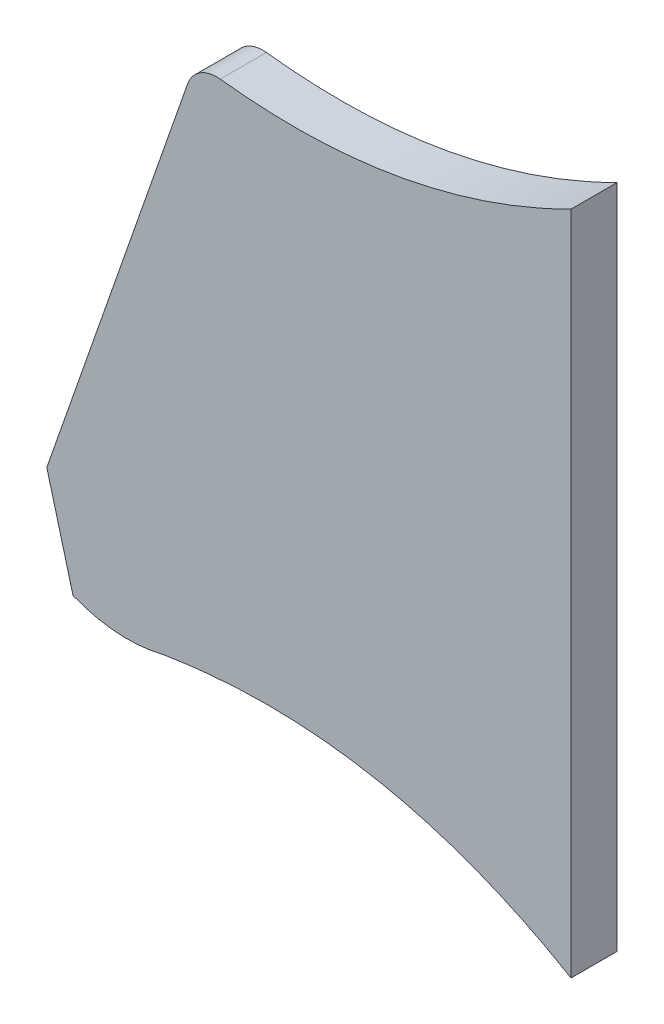
SolidWorks part; units mm, degrees
ref_plane "前视基准面" through (0, 0, 0) normal (0, 0, 1) x (1, 0, 0)
ref_plane "上视基准面" through (0, 0, 0) normal (0, 1, 0) x (1, 0, 0)
ref_plane "右视基准面" through (0, 0, 0) normal (1, 0, 0) x (0, 0, -1)
sketch "草图1" plane through (0, 0, 0) normal (0, 0, 1) x (1, 0, 0)
  line L0 (18.4197, -31.18) -> (-18.9977, -2.6487)
  line L1 (-4.1273, 31.6164) -> (18.9977, 31.6164)
  line L2 (-18.9977, -2.6487) -> (-11.5165, 31.6164)
  line L3 (-4.1273, 31.6164) -> (-11.5165, 31.6164)
  line L4 (18.9977, -31.6164) -> (18.4197, -31.18)
  line L5 (18.9977, -31.6164) -> (18.9977, 31.6164)
extrude "凸台-拉伸1" add sketch "草图1" along normal blind 3
sketch "草图2" plane through (0, 0, 3) normal (0, 0, 1) x (1, 0, 0)
  line L0 (18.9977, 31.6164) -> (18.9977, 39.6164)
  line L1 (18.9977, 39.6164) -> (-11.5165, 31.6164)
  line L2 (-11.5165, 31.6164) -> (18.9977, 31.6164)
  dimension "D1" = 8
extrude "凸台-拉伸2" add sketch "草图2" against normal up to surface (3 mm away) up to face at (5.1802, -0.4425, 0)
sketch "草图3" plane through (0, 0, 3) normal (0, 0, 1) x (1, 0, 0)
  line L0 (-18.9977, -2.6487) -> (18.4197, -31.18) construction
  line L1 (-18.9977, -2.6487) -> (18.4197, -31.18)
  line L2 (18.4197, -31.18) -> (18.9977, -31.6164) construction
  line L3 (18.4197, -31.18) -> (18.9977, -31.6164)
  spline S0 degree 3 poles (-18.9977, -2.6487) (-4.9094, -6.6648) (12.9602, -16.654) (18.9977, -31.6164) knots 0 0 0 0 0.839418 0.839418 0.839418 0.839418
extrude "切除-拉伸1" cut sketch "草图3" against normal blind 10
sketch "草图4" plane through (0, 0, 3) normal (0, 0, 1) x (1, 0, 0)
  line L0 (18.9977, 39.6164) -> (-11.5165, 31.6164) construction
  line L1 (18.9977, 39.6164) -> (-11.5165, 31.6164)
  spline S0 degree 2 poles (-11.5165, 31.6164) (5.4512, 29.7877) (18.9977, 39.6164) knots 0 0 0 1 1 1
extrude "切除-拉伸2" cut sketch "草图4" against normal blind 10
fillet "圆角1" radius 2 2 edges
sketch "草图5" plane through (0, 0, 3) normal (0, 0, 1) x (1, 0, 0)
  line L0 (-11.893, 29.892) -> (-18.6023, -0.8377) construction
  line L1 (-15.2477, 14.5271) -> (-18.6023, -0.8377)
  line L2 (-15.2477, 14.5271) -> (-5.3496, -8.0356)
  arc A2 (-18.6023, -0.8377) -> (-17.2465, -3.1728) centre (-16.6484, -1.2644) ccw construction
  arc A3 (-18.6023, -0.8377) -> (-17.2465, -3.1728) centre (-16.6484, -1.2644) ccw
  spline S0 degree 3 poles (-2928.8472, -519.4366) (3261.8242, -52.6008) (-3274.341, 435.7639) (2901.1179, -683.4599) knots -4.305527 -4.305527 -4.305527 -4.305527 5.571871 5.571871 5.571871 5.571871 only from (18.9977, -31.6164) to (-17.2465, -3.1728) construction
  spline S1 degree 3 poles (-5.3496, -8.0356) (-9.3409, -6.0038) (-13.4058, -4.3765) (-17.2465, -3.1728) knots 0.580679 0.580679 0.580679 0.580679 0.804995 0.804995 0.804995 0.804995
extrude "切除-拉伸3" cut sketch "草图5" against normal blind 10
sketch "草图6" plane through (0, 0, 3) normal (0, 0, 1) x (1, 0, 0)
  line L0 (18.9977, -31.6164) -> (18.9977, 39.6164) construction
  line L1 (18.9977, -31.6164) -> (18.9977, -24.042)
  spline S0 degree 3 poles (-2928.7675, -519.4306) (3265.9626, -52.2803) (-3283.1776, 436.4209) (2913.6883, -685.7371) knots -4.305484 -4.305484 -4.305484 -4.305484 5.578563 5.578563 5.578563 5.578563 only from (18.9977, -31.6164) to (-5.3496, -8.0356) construction
  spline S1 degree 3 poles (18.9977, -31.6164) (14.8212, -21.2659) (4.9826, -13.2953) (-5.3496, -8.0356) knots 0 0 0 0 0.580679 0.580679 0.580679 0.580679
  spline S2 degree 2 poles (-5.3496, -8.0356) (10.7128, -10.6039) (18.9977, -24.042) knots 0 0 0 1 1 1
extrude "切除-拉伸4" cut sketch "草图6" against normal blind 10
sketch "草图7" plane through (0, 0, 3) normal (0, 0, 1) x (1, 0, 0)
  line L0 (-5.3496, -8.0356) -> (-15.2477, 14.5271) construction
  line L1 (-5.3496, -8.0356) -> (-7.5011, -3.1311)
  line L2 (18.9977, -24.042) -> (18.9977, 39.6164) construction
  line L3 (18.9977, -24.042) -> (18.9977, 39.6164)
  parabola Q0 (18.9977, -24.042) -> (-5.3496, -8.0356) focus (0.5756, -26.9247) apex (9.8018, -14.0303) construction
  parabola Q1 (18.9977, -24.042) -> (-5.3496, -8.0356) focus (0.5756, -26.9247) apex (9.8018, -14.0303)
  spline S0 degree 2 poles (-7.5011, -3.1311) (8.5342, -3.7064) (18.9977, -15.7287) knots 0 0 0 1 1 1
  line M1 (-15.2477, 14.5271) -> (-5.3496, -8.0356)
  spline M2 degree 2 poles (18.9977, -24.042) (10.7128, -10.6039) (-5.3496, -8.0356) knots 0 0 0 1 1 1
  line M3 (18.9977, -24.042) -> (18.9977, 39.6164)
extrude "切除-拉伸5" cut sketch "草图7" against normal blind 10 contours S0 M1 M2 M3
sketch "草图9" plane through (0, 0, 3) normal (0, 0, 1) x (1, 0, 0)
  line L0 (-15.2477, 14.5271) -> (-5.3931, 31.338)
  line L1 (-11.893, 29.892) -> (-15.2477, 14.5271) construction
  line L2 (-11.893, 29.892) -> (-15.2477, 14.5271)
  arc A0 (-9.7926, 31.4601) -> (-11.893, 29.892) centre (-9.9391, 29.4654) ccw construction
  arc A1 (-9.7926, 31.4601) -> (-11.893, 29.892) centre (-9.9391, 29.4654) ccw
  parabola Q0 (-9.7926, 31.4601) -> (18.9977, 39.6164) focus (-0.0193, 52.6524) apex (5.7423, 33.0205) construction
  parabola Q1 (-9.7926, 31.4601) -> (18.9977, 39.6164) focus (-0.0193, 52.6524) apex (5.7423, 33.0205) construction
  parabola Q2 (-9.7926, 31.4601) -> (-5.3931, 31.338) focus (-0.0193, 52.6524) apex (5.7423, 33.0205)
extrude "切除-拉伸6" cut sketch "草图9" against normal blind 10
sketch "草图10" plane through (0, 0, 3) normal (0, 0, 1) x (1, 0, 0)
  line L0 (-15.2477, 14.5271) -> (-5.3931, 31.338) construction
  line L1 (-15.2477, 14.5271) -> (-5.3931, 31.338)
  line L2 (-5.3931, 31.338) -> (-13.424, 10.37)
  line L3 (-7.5011, -3.1311) -> (-15.2477, 14.5271) construction
  line L4 (-13.424, 10.37) -> (-15.2477, 14.5271)
extrude "切除-拉伸7" cut sketch "草图10" against normal blind 10
sketch "草图11" plane through (0, 0, 3) normal (0, 0, 1) x (1, 0, 0)
  line L0 (-7.5011, -3.1311) -> (-13.424, 10.37) construction
  line L1 (-7.5011, -3.1311) -> (-13.424, 10.37)
  line L2 (-13.424, 10.37) -> (-5.3931, 31.338) construction
  line L3 (-13.424, 10.37) -> (-5.3931, 31.338)
  line L4 (-7.5011, -3.1311) -> (-13.424, 3.6194)
  line L5 (-13.424, 3.6194) -> (-13.424, 16.6194)
  line L6 (-13.424, 16.6194) -> (-5.3931, 31.338)
  line M2 (-5.3931, 31.338) -> (-13.424, 10.37)
  line M3 (-13.424, 10.37) -> (-7.5011, -3.1311)
extrude "凸台-拉伸3" add sketch "草图11" against normal up to surface (3 mm away) contours L5 L4 M3 | L6 L5 M2 up to face at (7.6352, 9.9734, 0)
sketch "草图12" plane through (0, 0, 3) normal (0, 0, 1) x (1, 0, 0)
  line L0 (18.9977, -15.7287) -> (18.9977, -16.3787)
  parabola Q0 (-7.5011, -3.1311) -> (18.9977, -15.7287) focus (0.0241, -21.9021) apex (7.4222, -6.7033) construction
  parabola Q1 (-7.5011, -3.1311) -> (18.9977, -15.7287) focus (0.0241, -21.9021) apex (7.4222, -6.7033)
  spline S0 degree 2 poles (-7.5011, -3.1311) (8.2316, -4.862) (18.9977, -16.3787) knots 0 0 0 1 1 1
extrude "凸台-拉伸4" add sketch "草图12" against normal up to surface (3 mm away) up to face at (3.2804, 5.857, 0)
sketch "草图14" plane through (0, 0, 3) normal (0, 0, 1) x (1, 0, 0)
  line L0 (-13.424, 16.6194) -> (-5.3931, 31.338) construction
  line L1 (-13.424, 16.6194) -> (-5.3931, 31.338)
  line L2 (-13.424, 3.6194) -> (-13.424, 16.6194) construction
  line L3 (-13.424, 3.6194) -> (-13.424, 16.6194)
  line L4 (-7.5011, -3.1311) -> (-13.424, 3.6194) construction
  line L5 (-7.5011, -3.1311) -> (-13.424, 3.6194)
  line L6 (-7.5011, -3.1311) -> (-15.0881, 3.6194)
  line L7 (-15.0881, 3.6194) -> (-15.0881, 18.6192)
  line L8 (-15.0881, 18.6192) -> (-5.3931, 31.338)
extrude "凸台-拉伸5" add sketch "草图14" against normal up to surface (3 mm away) up to face at (-1.136, 7.8483, 0)
sketch "草图15" plane through (0, 0, 3) normal (0, 0, 1) x (1, 0, 0)
  line L0 (-5.3931, 31.338) -> (-15.0881, 18.6192) construction
  line L1 (-5.3931, 31.338) -> (-15.0881, 18.6192)
  line L2 (-5.3931, 31.338) -> (-15.0881, 14.4684)
  line L3 (-15.0881, 18.6192) -> (-15.0881, 3.6194) construction
  line L4 (-15.0881, 14.4684) -> (-15.0881, 18.6192)
extrude "切除-拉伸8" cut sketch "草图15" against normal blind 10
sketch "草图16" plane through (0, 0, 3) normal (0, 0, 1) x (1, 0, 0)
  line L0 (18.9977, -16.3787) -> (18.9977, 39.6164) construction
  line L1 (18.9977, -16.3787) -> (18.9977, -10.9026)
  parabola Q0 (-7.5011, -3.1311) -> (18.9977, -16.3787) focus (-1.8424, -25.2466) apex (7.2064, -7.4175) construction
  parabola Q1 (-7.5011, -3.1311) -> (18.9977, -16.3787) focus (-1.8424, -25.2466) apex (7.2064, -7.4175)
  spline S0 degree 2 poles (-7.5011, -3.1311) (7.0935, -2.5935) (18.9977, -10.9026) knots 0 0 0 1 1 1
extrude "切除-拉伸9" cut sketch "草图16" against normal blind 10
sketch "草图17" plane through (0, 0, 3) normal (0, 0, 1) x (1, 0, 0)
  line L0 (18.9977, -10.9026) -> (18.9977, 39.6164) construction
  line L1 (18.9977, -10.9026) -> (18.9977, -8.0852)
  parabola Q0 (18.9977, -10.9026) -> (-7.5011, -3.1311) focus (0.816, -24.646) apex (6.8143, -4.9227) construction
  parabola Q1 (18.9977, -10.9026) -> (-7.5011, -3.1311) focus (0.816, -24.646) apex (6.8143, -4.9227)
  spline S0 degree 2 poles (-7.5011, -3.1311) (6.6872, -0.8041) (18.9977, -8.0852) knots 0 0 0 1 1 1
extrude "切除-拉伸10" cut sketch "草图17" against normal blind 10
sketch "草图18" plane through (0, 0, 3) normal (0, 0, 1) x (1, 0, 0)
  line L0 (-15.0881, 3.6194) -> (-13.381, -2.7449)
  line L6 (-15.0881, 3.6194) -> (-7.5011, -3.1311) construction
  line L7 (-15.0881, 3.6194) -> (-7.5011, -3.1311)
  spline S0 degree 2 poles (-13.381, -2.7449) (-10.489, -3.877) (-7.5011, -3.1311) knots 0 0 0 1 1 1
extrude "凸台-拉伸7" add sketch "草图18" against normal up to surface (3 mm away) up to face at (-0.8458, 12.0669, 0)
sketch "草图19" plane through (0, 0, 3) normal (0, 0, 1) x (1, 0, 0)
  line L0 (-15.0881, 14.4684) -> (-5.3931, 31.338) construction
  line L1 (-15.0881, 14.4684) -> (-13.5933, 17.0694)
  line L2 (-15.0881, 14.4684) -> (-15.0881, 3.6194) construction
  line L3 (-15.0881, 14.4684) -> (-15.0881, 11.4684)
  line L4 (-15.0881, 14.4684) -> (-15.0881, 11.4684)
  line L5 (-15.0881, 14.4684) -> (-13.5933, 17.0694)
  line L6 (-13.5933, 17.0694) -> (-15.0881, 11.4684)
  line M1 (-15.0881, 14.4684) -> (-15.0881, 3.6194)
  line M7 (-5.3931, 31.338) -> (-15.0881, 14.4684)
extrude "切除-拉伸11" cut sketch "草图19" against normal blind 10 contours L6 M7 M1
sketch "草图20" plane through (0, 0, 3) normal (0, 0, 1) x (1, 0, 0)
  line L0 (18.9977, -8.0852) -> (18.9977, 39.6164) construction
  line L1 (18.9977, 35.2073) -> (18.9977, 39.6164)
  parabola Q0 (-5.3931, 31.338) -> (18.9977, 39.6164) focus (-0.0193, 52.6524) apex (5.7423, 33.0205) construction
  parabola Q1 (-5.3931, 31.338) -> (18.9977, 39.6164) focus (-0.0193, 52.6524) apex (5.7423, 33.0205)
  spline S0 degree 2 poles (-5.3931, 31.338) (7.3954, 29.3585) (18.9977, 35.2073) knots 0 0 0 1 1 1
extrude "切除-拉伸12" cut sketch "草图20" against normal blind 10
sketch "草图22" plane through (0, 0, 3) normal (0, 0, 1) x (1, 0, 0)
  line L0 (-5.3931, 31.338) -> (-15.0881, 3.6194)
  line L1 (-13.5933, 17.0694) -> (-5.3931, 31.338) construction
  line L2 (-13.5933, 17.0694) -> (-5.3931, 31.338)
  line L3 (-13.5933, 17.0694) -> (-15.0881, 11.4684) construction
  line L4 (-13.5933, 17.0694) -> (-15.0881, 11.4684)
  line L5 (-15.0881, 11.4684) -> (-15.0881, 3.6194) construction
  line L6 (-15.0881, 11.4684) -> (-15.0881, 3.6194)
extrude "切除-拉伸13" cut sketch "草图22" against normal blind 10
fillet "圆角2" radius 2 1 edges
